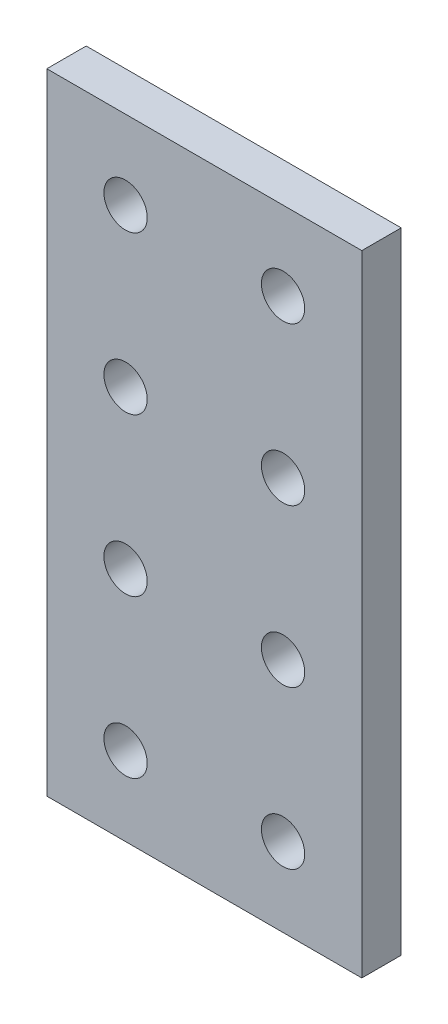
SolidWorks part; units mm, degrees
ref_plane "Plan de face" through (0, 0, 0) normal (0, 0, 1) x (1, 0, 0)
ref_plane "Plan de dessus" through (0, 0, 0) normal (0, 1, 0) x (1, 0, 0)
ref_plane "Plan de droite" through (0, 0, 0) normal (1, 0, 0) x (0, 0, -1)
sketch "Esquisse1" plane through (0, 0, 0) normal (0, 0, 1) x (1, 0, 0)
  line L1 (-60.3499, 19.4444) -> (-20.3499, 19.4444)
  line L2 (-60.3499, 19.4444) -> (-60.3499, -60.5556)
  line L3 (-60.3499, -60.5556) -> (-20.3499, -60.5556)
  line L4 (-20.3499, 19.4444) -> (-20.3499, -60.5556)
  circle A0 centre (-50.3499, 9.4444) radius 2.75
  circle A1 centre (-30.3499, 9.4444) radius 2.75
  circle A2 centre (-30.3499, -10.5556) radius 2.75
  circle A3 centre (-30.3499, -30.5556) radius 2.75
  circle A4 centre (-30.3499, -50.5556) radius 2.75
  circle A5 centre (-50.3499, -10.5556) radius 2.75
  circle A6 centre (-50.3499, -30.5556) radius 2.75
  circle A7 centre (-50.3499, -50.5556) radius 2.75
  dimension "D3" = 5.5
  dimension "D1" = 80
  dimension "D2" = 40
  dimension "D4" = 10
  dimension "D5" = 10
  dimension "D6" = 2
  dimension "D7" = 4
extrude "Boss.-Extru.1" add sketch "Esquisse1" along normal blind 5
